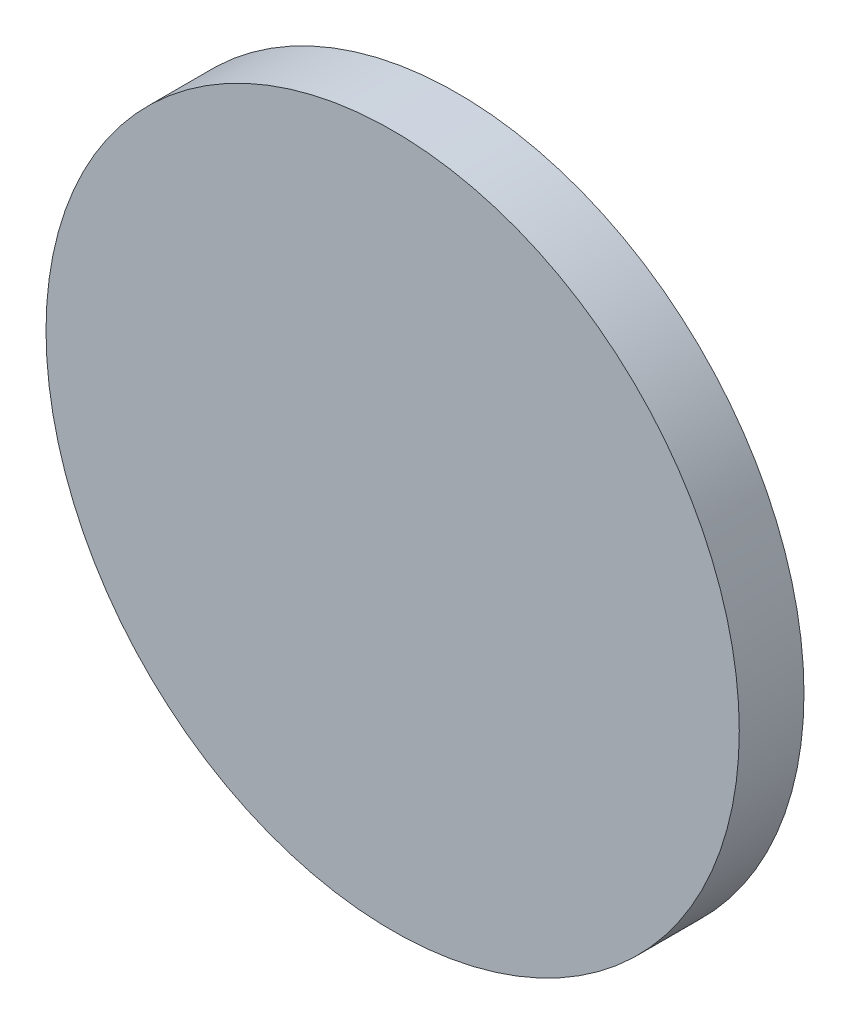
SolidWorks part; units mm, degrees
ref_plane "Front Plane" through (0, 0, 0) normal (0, 0, 1) x (1, 0, 0)
ref_plane "Top Plane" through (0, 0, 0) normal (0, 1, 0) x (1, 0, 0)
ref_plane "Right Plane" through (0, 0, 0) normal (1, 0, 0) x (0, 0, -1)
sketch "Sketch1" plane through (0, 0, 0) normal (0, 0, 1) x (1, 0, 0)
  circle A0 centre (0, 0) radius 37.5
  dimension "D1" = 75
extrude "Boss-Extrude1" add sketch "Sketch1" along normal blind 7
